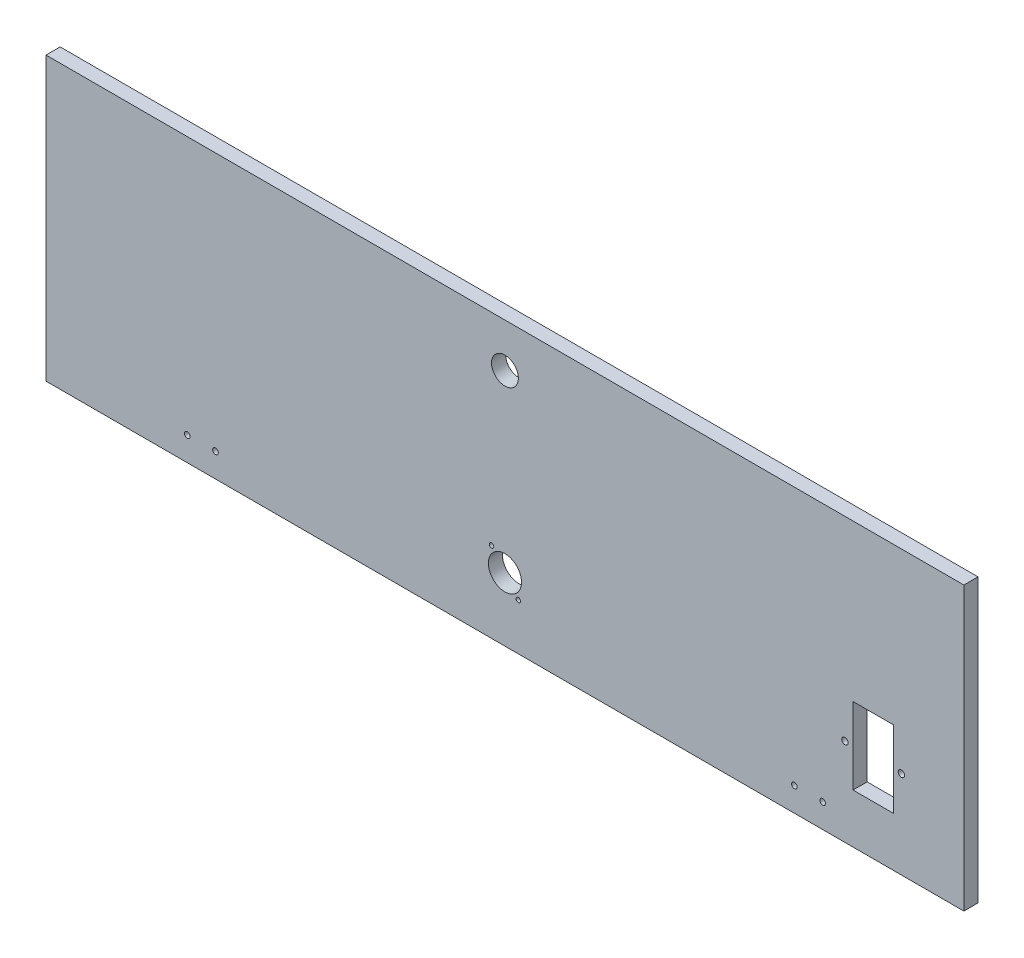
SolidWorks part; units mm, degrees
ref_plane "Plan de face" through (0, 0, 0) normal (0, 0, 1) x (1, 0, 0)
ref_plane "Plan de dessus" through (0, 0, 0) normal (0, 1, 0) x (1, 0, 0)
ref_plane "Plan de droite" through (0, 0, 0) normal (1, 0, 0) x (0, 0, -1)
sketch "Esquisse1" plane through (0, 0, 0) normal (0, 0, 1) x (1, 0, 0)
  line L1 (0, 0) -> (650, 0)
  line L2 (0, 0) -> (0, 200)
  line L3 (0, 200) -> (650, 200)
  line L4 (650, 0) -> (650, 200)
  dimension "D1" = 200
  dimension "D2" = 650
extrude "Boss.-Extru.1" add sketch "Esquisse1" along normal blind 10
sketch "Esquisse2" plane through (0, 0, 10) normal (0, 0, 1) x (1, 0, 0)
  line L4 (0, 200) -> (0, 0) construction
  line L5 (650, 0) -> (650, 200) construction
  line L6 (0, 0) -> (650, 0) construction
  circle A0 centre (100, 17) radius 2
  circle A1 centre (120, 17) radius 2
  circle A2 centre (530, 17) radius 2
  circle A3 centre (550, 17) radius 2
  dimension "D1" = 4
  dimension "D2" = 4
  dimension "D3" = 4
  dimension "D4" = 4
  dimension "D5" = 20
  dimension "D6" = 20
  dimension "D7" = 100
  dimension "D8" = 100
  dimension "D9" = 17
  dimension "D10" = 17
  dimension "D11" = 17
  dimension "D12" = 17
extrude "Enlèv. mat.-Extru.1" cut sketch "Esquisse2" against normal blind 10
sketch "Esquisse3" plane through (0, 0, 10) normal (0, 0, 1) x (1, 0, 0)
  line L0 (0, 0) -> (650, 0) construction
  line L1 (334.5004, 33.0006) -> (325, 45)
  line L2 (325, 45) -> (315.4996, 56.9994)
  line L3 (325, 45) -> (265.8175, 45)
  line L4 (325, 45) -> (364.3682, 45)
  line L5 (650, 0) -> (650, 200) construction
  line L6 (571.5, 35) -> (600, 35)
  line L7 (571.5, 35) -> (571.5, 89.3)
  line L8 (571.5, 89.3) -> (600, 89.3)
  line L9 (600, 35) -> (600, 89.3)
  circle A0 centre (325, 45) radius 11.75
  circle A1 centre (315.4996, 56.9994) radius 1.6
  circle A2 centre (334.5004, 33.0006) radius 1.6
  circle A3 centre (565.75, 62.15) radius 2.25
  circle A4 centre (605.75, 62.15) radius 2.25
  point P4 (325, 0)
  point P19 (585.75, 89.3)
  point P20 (571.5, 62.15)
  dimension "D1" = 23.5
  dimension "D4" = 3.2
  dimension "D5" = 3.2
  dimension "D14" = 4.5
  dimension "D15" = 4.5
  dimension "D2" = 0
  dimension "D3" = 45
  dimension "D6" = 30.61
  dimension "D7" = 15.305
  dimension "D8" = 51.63
  dimension "D9" = 180
  dimension "D10" = 51.63
  dimension "D11" = 15.305
  dimension "D12" = 28.5
  dimension "D13" = 54.3
  dimension "D16" = 40
  dimension "D17" = 20
  dimension "D18" = 0
  dimension "D19" = 35
  dimension "D20" = 50
  dimension "D21" = 20
extrude "Enlèv. mat.-Extru.2" cut sketch "Esquisse3" against normal blind 10
sketch "Esquisse4" plane through (0, 0, 10) normal (0, 0, 1) x (1, 0, 0)
  line L0 (650, 200) -> (0, 200) construction
  circle A0 centre (325, 169) radius 9.5
  point P4 (325, 200)
  dimension "D1" = 19
  dimension "D3" = 31
  dimension "D2" = 0
extrude "Enlèv. mat.-Extru.3" cut sketch "Esquisse4" against normal blind 10
sketch "Esquisse5" plane through (0, 0, 0) normal (0, 0, 1) x (1, 0, 0)
  line L0 (650, 200) -> (0, 200) construction
  line L1 (650, 200) -> (0, 200) construction
  line L2 (0, 200) -> (0, 0) construction
  line L3 (650, 0) -> (650, 200) construction
  circle A0 centre (341, 169) radius 1
  circle A1 centre (309, 169) radius 1
  circle A2 centre (125, 193) radius 1
  circle A3 centre (105, 193) radius 1
  circle A4 centre (545, 193) radius 1
  circle A5 centre (525, 193) radius 1
  point P6 (325, 200)
  dimension "D2" = 2
  dimension "D3" = 2
  dimension "D7" = 2
  dimension "D8" = 2
  dimension "D9" = 2
  dimension "D10" = 2
  dimension "D1" = 32
  dimension "D4" = 16
  dimension "D5" = 31
  dimension "D6" = 31
  dimension "D11" = 20
  dimension "D12" = 7
  dimension "D13" = 7
  dimension "D14" = 105
  dimension "D15" = 7
  dimension "D16" = 7
  dimension "D17" = 20
  dimension "D18" = 105
extrude "Enlèv. mat.-Extru.4" cut sketch "Esquisse5" along normal blind 2
